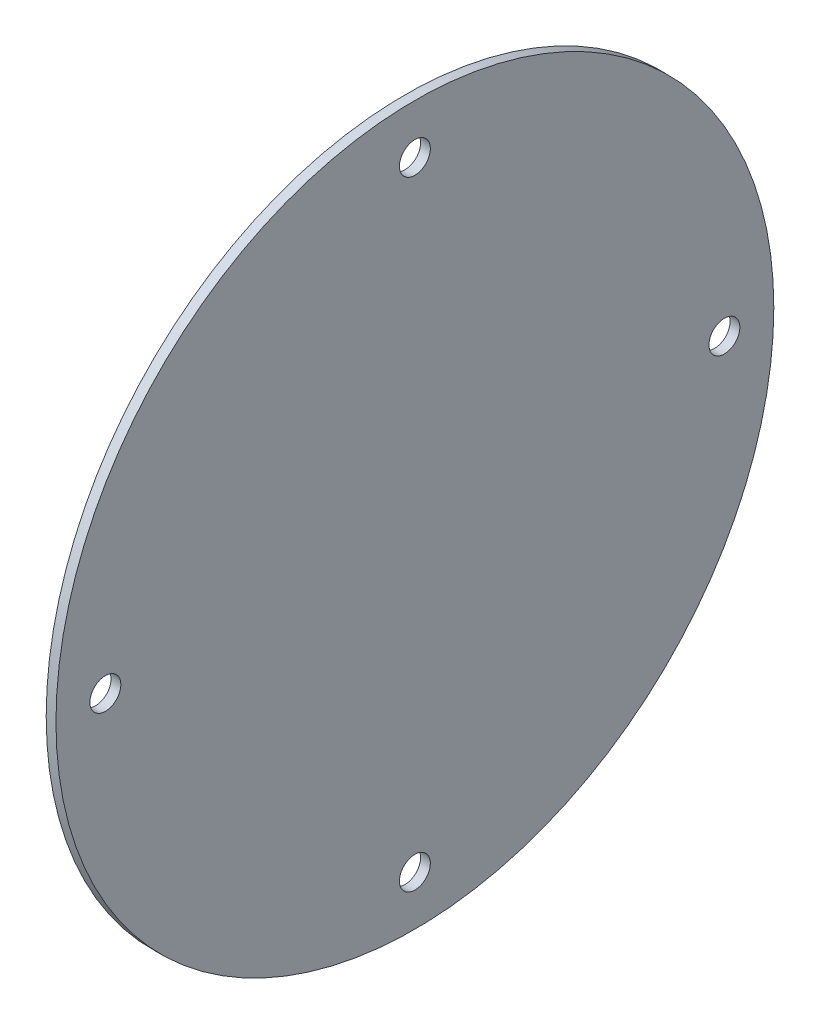
SolidWorks part; units mm, degrees
ref_plane "Front Plane" through (0, 0, 0) normal (1, 0, 0) x (0, 1, 0)
ref_plane "Top Plane" through (0, 0, 0) normal (0, 0, 1) x (0, 1, 0)
ref_plane "Right Plane" through (0, 0, 0) normal (0, 1, 0) x (-1, 0, 0)
sketch "Sketch1" plane through (0, 0, 0) normal (1, 0, 0) x (0, 1, 0)
  circle A0 centre (0, 0) radius 73.787
  dimension "D1" = 147.574
extrude "Boss-Extrude1" add sketch "Sketch1" along normal blind 2.0066
sketch "Sketch2" plane through (2.0066, 0, 0) normal (1, 0, 0) x (0, 0, -1)
  line L0 (-73.787, 0) -> (-63.627, 0)
  circle A0 centre (0, 0) radius 73.787 construction
  circle A1 centre (-63.627, 0) radius 3.175
  dimension "D2" = 6.35
  dimension "D1" = 10.16
extrude "Cut-Extrude1" cut sketch "Sketch2" against normal through all contours A1
pattern_circular "CirPattern1" count 4 over 360 about axis through (0, 0, 0) along (1, 0, 0) of "Cut-Extrude1"
